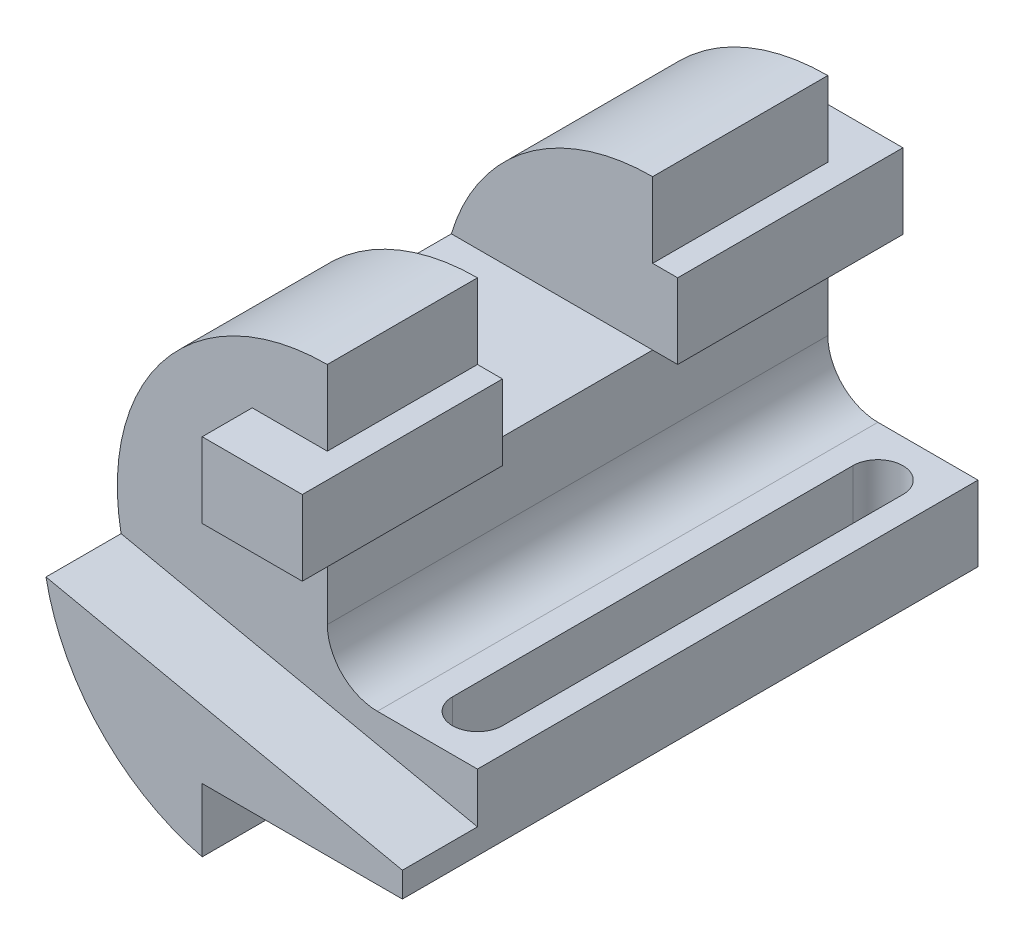
SolidWorks part; units mm, degrees
material "1060 Alloy"
ref_plane "Front Plane" through (0, 0, 0) normal (0, 0, 1) x (1, 0, 0)
ref_plane "Top Plane" through (0, 0, 0) normal (0, 1, 0) x (1, 0, 0)
ref_plane "Right Plane" through (0, 0, 0) normal (1, 0, 0) x (0, 0, -1)
sketch "Sketch1" plane through (0, 0, 0) normal (0, 0, 1) x (1, 0, 0)
  line L0 (0, 0) -> (0, 12.7019)
  line L1 (0, 12.7019) -> (40, 12.7019)
  line L2 (40, 12.7019) -> (40, 27.7019)
  line L3 (40, 27.7019) -> (20, 27.7019)
  line L4 (10, 37.7019) -> (10, 52.7019)
  line L5 (10, 52.7019) -> (15, 52.7019)
  line L6 (15, 52.7019) -> (15, 67.7019)
  line L7 (15, 67.7019) -> (10, 67.7019)
  line L8 (10, 67.7019) -> (10, 82.7019)
  arc A0 (10, 82.7019) -> (0, 0) centre (10, 40.7464) ccw
  arc A1 (10, 37.7019) -> (20, 27.7019) centre (20, 37.7019) ccw
  dimension "D1" = 40
  dimension "D7" = 10
  dimension "D10" = 41.9556
  dimension "D2" = 15
  dimension "D3" = 55
  dimension "D4" = 5
  dimension "D5" = 15
  dimension "D6" = 15
  dimension "D8" = 10
  dimension "D9" = 20
  dimension "D11" = 12.7019
extrude "Boss-Extrude1" add sketch "Sketch1" along normal blind 100
sketch "Sketch2" plane through (15, 0, 0) normal (1, 0, 0) x (0, 0, -1)
  line L0 (-100, 82.7019) -> (0, 82.7019) construction
  line L1 (-70, 82.7019) -> (-35, 82.7019)
  line L2 (-70, 82.7019) -> (-70, 52.7019)
  line L3 (-70, 52.7019) -> (-35, 52.7019)
  line L4 (-35, 82.7019) -> (-35, 52.7019)
  line L5 (-100, 52.7019) -> (0, 52.7019) construction
  dimension "D1" = 35
  dimension "D2" = 30
extrude "Cut-Extrude1" cut sketch "Sketch2" against normal through all
sketch "Sketch3" plane through (0, 0, 100) normal (0, 0, 1) x (1, 0, 0)
  line L0 (0, 12.7019) -> (40, 12.7019) construction
  line L1 (15, 67.7019) -> (-5, 67.7019)
  line L2 (15, 67.7019) -> (15, 52.7019)
  line L3 (15, 52.7019) -> (-5, 52.7019)
  line L4 (-5, 67.7019) -> (-5, 52.7019)
  dimension "D1" = 20
  dimension "D2" = 40
extrude "Boss-Extrude2" add sketch "Sketch3" along normal blind 10
sketch "Sketch4" plane through (0, 0, 0) normal (0, 0, -1) x (-1, 0, 0)
  line L0 (0, 12.7019) -> (-40, 12.7019) construction
  line L1 (-15, 67.7019) -> (5, 67.7019)
  line L2 (-15, 67.7019) -> (-15, 52.7019)
  line L3 (-15, 52.7019) -> (5, 52.7019)
  line L4 (5, 67.7019) -> (5, 52.7019)
  dimension "D1" = 20
  dimension "D2" = 40
extrude "Boss-Extrude3" add sketch "Sketch4" along normal blind 10
sketch "Sketch5" plane through (0, 0, 100) normal (0, 0, 1) x (1, 0, 0)
  line L0 (40, 17.7019) -> (-31.2032, 32.8367)
  line L1 (40, 12.7019) -> (40, 27.7019) construction
  line L2 (40, 17.7019) -> (40, 12.7019)
  line L3 (40, 12.7019) -> (0, 12.7019)
  line L4 (0, 12.7019) -> (0, 0)
  arc A0 (10, 82.7019) -> (0, 0) centre (10, 40.7464) ccw construction
  arc A1 (-31.2032, 32.8367) -> (0, 0) centre (10, 40.7464) ccw
  dimension "D2" = 5
  dimension "D3" = 41.9556
  dimension "D1" = 78
extrude "Boss-Extrude4" add sketch "Sketch5" along normal blind 15
sketch "Sketch6" plane through (0, 27.7019, 0) normal (0, 1, 0) x (1, 0, 0)
  line L0 (30, -10) -> (30, -90) construction
  line L1 (40, 0) -> (20, 0) construction
  line L2 (35, -10) -> (35, -90)
  line L3 (25, -10) -> (25, -90)
  line L5 (40, -100) -> (40, 0) construction
  arc A0 (35, -10) -> (25, -10) centre (30, -10) ccw
  arc A1 (25, -90) -> (35, -90) centre (30, -90) ccw
  point P4 (30, -50)
  dimension "D3" = 10
  dimension "D4" = 10
  dimension "D1" = 10
  dimension "D2" = 80
extrude "Cut-Extrude2" cut sketch "Sketch6" against normal through all
equation "\"a\"= 50"
equation "\"b\"= 55"
equation "\"c\"= 35"
